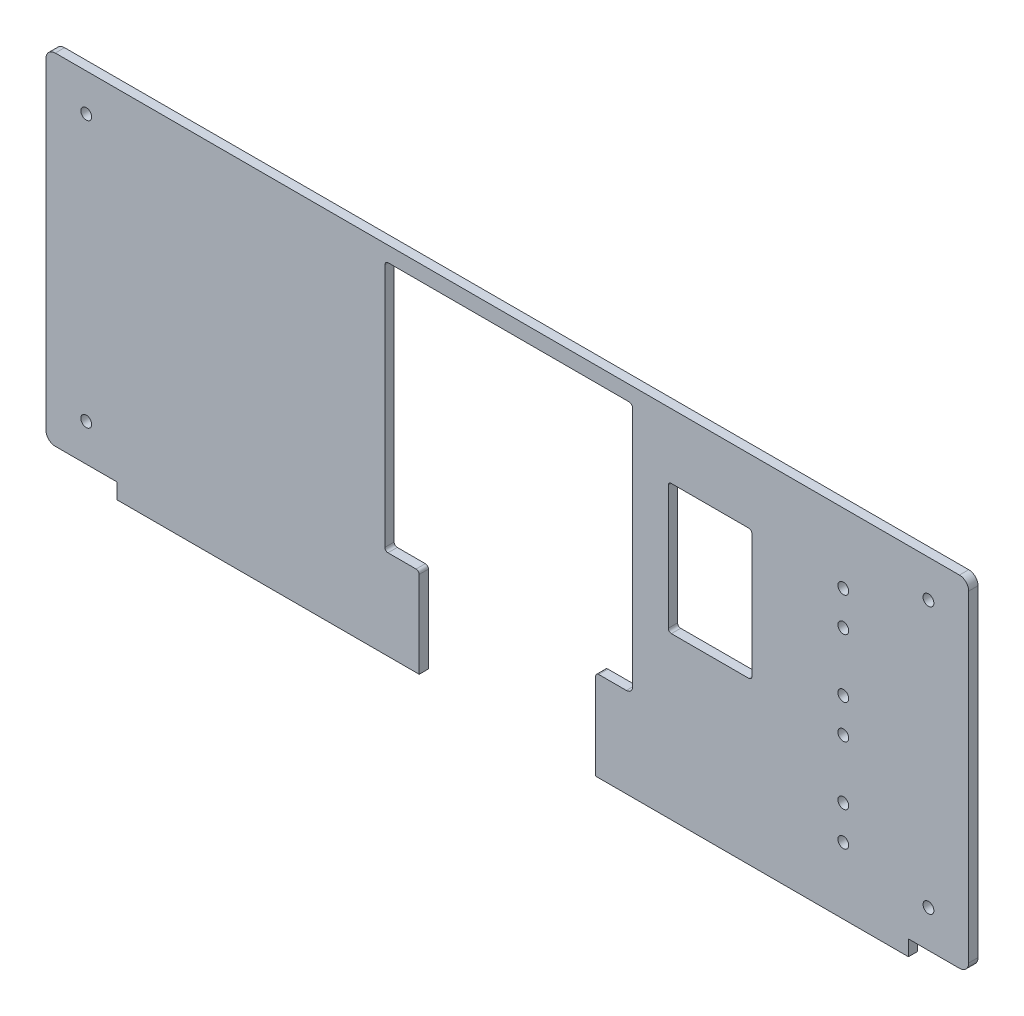
SolidWorks part; units mm, degrees
ref_plane "Front Plane" through (0, 0, 0) normal (0, 0, 1) x (1, 0, 0)
ref_plane "Top Plane" through (0, 0, 0) normal (0, 1, 0) x (1, 0, 0)
ref_plane "Right Plane" through (0, 0, 0) normal (1, 0, 0) x (0, 0, -1)
sketch "Sketch1" plane through (0, 0, 0) normal (0, 0, 1) x (1, 0, 0)
  line L0 (0, 219) -> (0, 211.4168) construction
  line L1 (-146, 334) -> (146, 334)
  line L2 (-149, 331) -> (-149, 227)
  line L3 (-146, 224) -> (-126, 224)
  line L4 (149, 331) -> (149, 227)
  line L5 (-39.5677, 248.9443) -> (-39.5677, 327.9522)
  line L6 (-136, 328.3773) -> (-136, 329.6139) construction
  line L7 (-38.4198, 329.1) -> (39.2845, 329.1)
  line L8 (40.4323, 327.9522) -> (40.4323, 249.9443)
  line L9 (129.5384, 224) -> (146, 224)
  line L10 (-126, 224) -> (-126, 219)
  line L11 (-126, 219) -> (-70, 219)
  line L12 (129.5384, 224) -> (129.5384, 219)
  line L13 (-70, 219) -> (-28.4693, 219)
  line L14 (52.9709, 313.1) -> (77.9709, 313.1)
  line L15 (51.9709, 312.1) -> (51.9709, 272.1)
  line L16 (52.9709, 271.1) -> (77.9709, 271.1)
  line L17 (78.9709, 312.1) -> (78.9709, 272.1)
  line L23 (129.5384, 219) -> (73.5384, 219)
  line L27 (38.4323, 247.9443) -> (29.5102, 247.9443)
  line L29 (52.9709, 312.1) -> (77.9709, 312.1) construction
  line L30 (52.9709, 312.1) -> (52.9709, 272.1) construction
  line L31 (52.9709, 272.1) -> (77.9709, 272.1) construction
  line L32 (77.9709, 312.1) -> (77.9709, 272.1) construction
  line L33 (136, 234.8142) -> (136, 235.2729) construction
  line L34 (73.5384, 219) -> (28.5102, 219)
  line L35 (28.5102, 219) -> (28.5102, 246.9443)
  line L36 (28.5102, 194.3457) -> (28.5102, 199.9122) construction
  line L37 (-28.4693, 196.0555) -> (-28.4693, 195.4713) construction
  line L38 (-28.4693, 219) -> (-28.4693, 246.9443)
  line L39 (-29.4693, 247.9443) -> (-38.5677, 247.9443)
  arc A0 (146, 224) -> (149, 227) centre (146, 227) ccw
  arc A1 (146, 334) -> (149, 331) centre (146, 331) cw
  arc A2 (-149, 227) -> (-146, 224) centre (-146, 227) ccw
  arc A3 (-146, 334) -> (-149, 331) centre (-146, 331) ccw
  circle A4 centre (-136, 322) radius 1.75
  circle A5 centre (-136, 236) radius 1.75
  circle A6 centre (136, 236) radius 1.75
  circle A7 centre (136, 322) radius 1.75
  arc A10 (39.2845, 329.1) -> (40.4323, 327.9522) centre (39.2845, 327.9522) cw
  arc A11 (-39.5677, 327.9522) -> (-38.4198, 329.1) centre (-38.4198, 327.9522) cw
  arc A12 (40.4323, 249.9443) -> (38.4323, 247.9443) centre (38.4323, 249.9443) cw
  arc A13 (51.9709, 272.1) -> (52.9709, 271.1) centre (52.9709, 272.1) ccw
  arc A23 (77.9709, 271.1) -> (78.9709, 272.1) centre (77.9709, 272.1) ccw
  arc A24 (77.9709, 313.1) -> (78.9709, 312.1) centre (77.9709, 312.1) cw
  arc A25 (52.9709, 313.1) -> (51.9709, 312.1) centre (52.9709, 312.1) ccw
  arc A28 (29.5102, 247.9443) -> (28.5102, 246.9443) centre (29.5102, 246.9443) ccw
  arc A29 (-39.5677, 248.9443) -> (-38.5677, 247.9443) centre (-38.5677, 248.9443) ccw
  arc A30 (-28.4693, 246.9443) -> (-29.4693, 247.9443) centre (-29.4693, 246.9443) ccw
  circle A31 centre (108.5, 311.54) radius 1.75
  circle A32 centre (108.5, 300.5) radius 1.75
  circle A33 centre (108.5, 281.54) radius 1.75
  circle A34 centre (108.5, 270.5) radius 1.75
  circle A35 centre (108.5, 251.54) radius 1.75
  circle A36 centre (108.5, 240.5) radius 1.75
  point P9 (149, 224)
  point P14 (-149, 224)
  point P17 (-149, 334)
  point P35 (40.4323, 224)
  point P38 (40.4323, 329.1)
  point P41 (-39.5677, 329.1)
  point P56 (-28.4693, 247.9443)
  point P70 (0, 0)
  point P78 (0, 180.3891)
  point P79 (40.4323, 224)
  dimension "D3" = 3
  dimension "D4" = 3.5
  dimension "D5" = 3.5
  dimension "D6" = 12
  dimension "D7" = 12
  dimension "D9" = 1
  dimension "D12" = 3.5
  dimension "D14" = 3.5
  dimension "D15" = 3.5
  dimension "D16" = 2
  dimension "D21" = 1
  dimension "D22" = 3.5
  dimension "D10" = 1
  dimension "D11" = 3.5
  dimension "D13" = 3.5
  dimension "D2" = 110
  dimension "D8" = 80
  dimension "D17" = 1
  dimension "D18" = 1
  dimension "D19" = 1
  dimension "D20" = 1
  dimension "D26" = 149
  dimension "D27" = 149
  dimension "D28" = 115
extrude "Boss-Extrude1" add sketch "Sketch1" along normal blind 3
